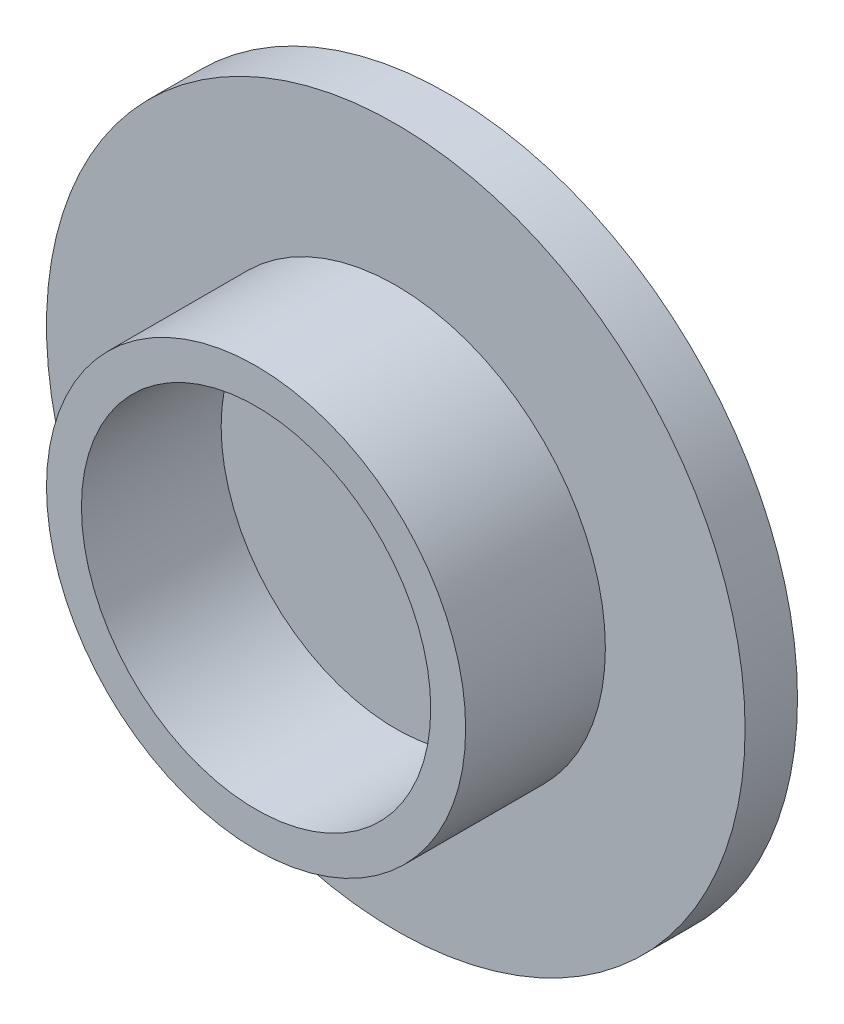
SolidWorks part; units mm, degrees
ref_plane "Front Plane" through (0, 0, 0) normal (0, 0, 1) x (1, 0, 0)
ref_plane "Top Plane" through (0, 0, 0) normal (0, 1, 0) x (1, 0, 0)
ref_plane "Right Plane" through (0, 0, 0) normal (1, 0, 0) x (0, 0, -1)
sketch "Sketch1" plane through (0, 0, 0) normal (0, 0, 1) x (1, 0, 0)
  circle A0 centre (0, 0) radius 20
  dimension "D1" = 40
extrude "Boss-Extrude1" add sketch "Sketch1" along normal blind 3
sketch "Sketch2" plane through (0, 0, 3) normal (0, 0, 1) x (1, 0, 0)
  circle A0 centre (0, 0) radius 10
  circle A1 centre (0, 0) radius 12
  dimension "D1" = 20
  dimension "D2" = 24
extrude "Boss-Extrude2" add sketch "Sketch2" along normal blind 8
